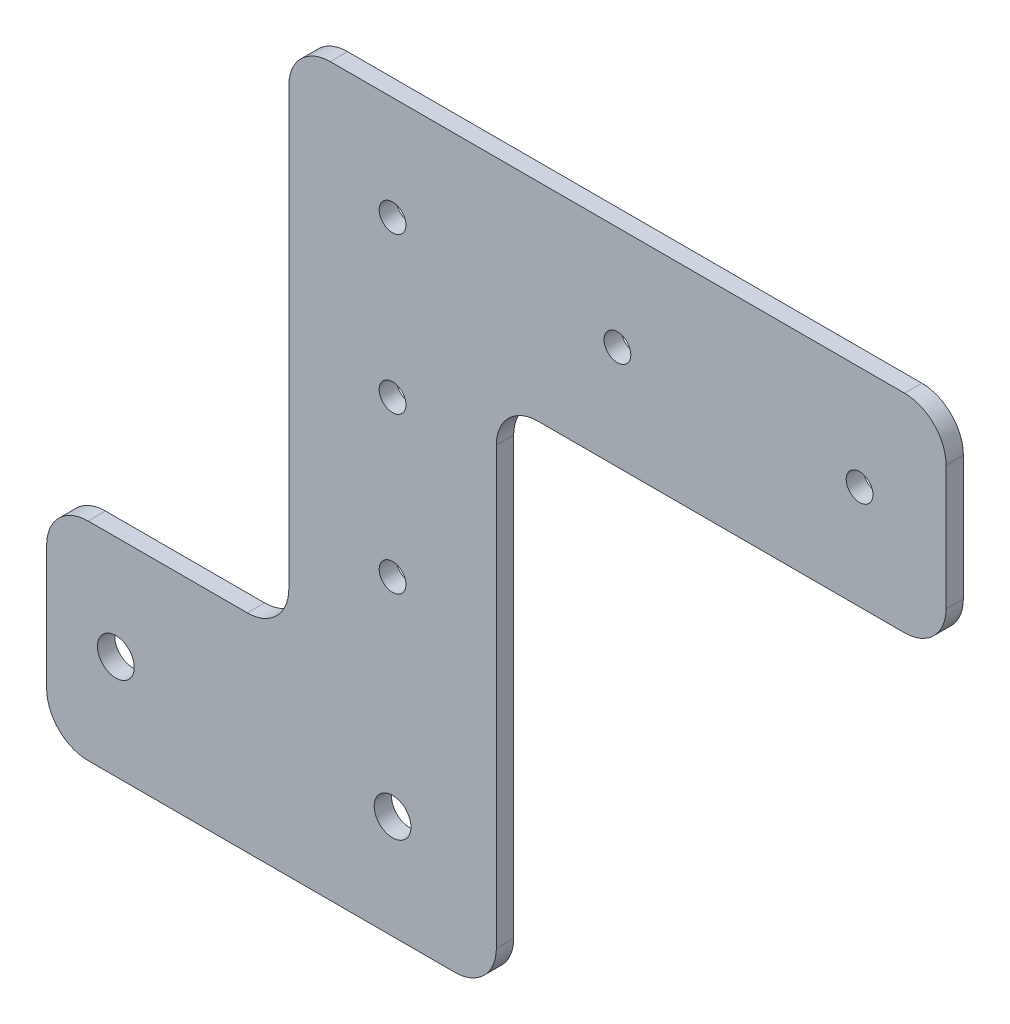
SolidWorks part; units mm, degrees
material "6061 Alloy"
ref_plane "Front Plane" through (0, 0, 0) normal (0, 0, 1) x (1, 0, 0)
ref_plane "Top Plane" through (0, 0, 0) normal (0, 1, 0) x (1, 0, 0)
ref_plane "Right Plane" through (0, 0, 0) normal (1, 0, 0) x (0, 0, -1)
sketch "Sketch1" plane through (0, 0, 0) normal (0, 0, 1) x (1, 0, 0)
  line L0 (0, 0) -> (82.55, 0)
  line L1 (82.55, 0) -> (82.55, 95.25)
  line L2 (82.55, 95.25) -> (165.1, 95.25)
  line L3 (0, 38.1) -> (44.45, 38.1)
  line L4 (44.45, 38.1) -> (44.45, 133.35)
  line L5 (44.45, 133.35) -> (165.1, 133.35)
  line L6 (0, 38.1) -> (0, 0)
  line L7 (165.1, 95.25) -> (165.1, 133.35)
  dimension "D2" = 133.35
  dimension "D3" = 82.55
  dimension "D4" = 120.65
  dimension "D1" = 38.1
extrude "Boss-Extrude1" add sketch "Sketch1" along normal blind 3.175
hole_wizard "#10 (0.1935) Diameter Hole1" positions "Sketch2" profile "Sketch3" hole size "#10" standard "ANSI Inch" end condition through all
sketch "Sketch2" plane through (0, 0, 3.175) normal (0, 0, 1) x (1, 0, 0)
  line L0 (0, 19.05) -> (63.5, 19.05) construction
  line L1 (0, 38.1) -> (0, 0) construction
  line L2 (165.1, 114.3) -> (63.5, 114.3) construction
  line L3 (165.1, 95.25) -> (165.1, 133.35) construction
  line L4 (63.5, 19.05) -> (63.5, 114.3) construction
  line L5 (44.45, 38.1) -> (82.55, 0) construction
  line L8 (165.1, 95.25) -> (165.1, 133.35) construction
  line L10 (0, 0) -> (82.55, 0) construction
  point P27 (63.5, 57.15)
  point P29 (63.5, 114.3)
  point P31 (149.225, 114.3)
  point P45 (104.775, 114.3)
  point P65 (63.5, 85.725)
  dimension "D1" = 28.575
  dimension "D3" = 15.875
  dimension "D4" = 60.325
  dimension "D6" = 57.15
sketch "Sketch3" plane through (63.5, 85.725, 3.175) normal (1, 0, 0) x (0, -1, 0)
  line L0 (0, 0) -> (0, 3.175)
  line L1 (0, 3.175) -> (2.4574, 3.175)
  line L2 (2.4574, 3.175) -> (2.4574, 0)
  line L5 (2.4574, 0) -> (0, 0)
  line L11 (0, -6.35) -> (0, 107.95) construction
  dimension "Thru Hole Dia." = 4.9149
  dimension "Thru Hole Depth" = 3.175
hole_wizard "1/4 Clearance Hole2" positions "Sketch4" profile "Sketch5" hole size "1/4" standard "ANSI Inch" end condition through all
sketch "Sketch4" plane through (0, 0, 3.175) normal (0, 0, 1) x (1, 0, 0)
  line L2 (0, 19.05) -> (82.55, 19.05) construction
  line L3 (0, 38.1) -> (0, 0) construction
  line L4 (82.55, 0) -> (82.55, 95.25) construction
  point P0 (12.7, 19.05)
  point P17 (63.5, 19.05)
  dimension "D1" = 19.05
  dimension "D2" = 69.85
sketch "Sketch5" plane through (12.7, 19.05, 3.175) normal (1, 0, 0) x (0, -1, 0)
  line L0 (0, 0) -> (0, 3.175)
  line L1 (0, 3.175) -> (3.3782, 3.175)
  line L2 (3.3782, 3.175) -> (3.3782, 0)
  line L5 (3.3782, 0) -> (0, 0)
  line L11 (0, -6.35) -> (0, 107.95) construction
  dimension "Thru Hole Dia." = 6.7564
  dimension "Thru Hole Depth" = 3.175
fillet "Fillet1" radius 7.62 8 edges at (0, 38.1, 1.5875) (44.45, 38.1, 1.5875) (44.45, 133.35, 1.5875) (165.1, 133.35, 1.5875) (165.1, 95.25, 1.5875) (82.55, 0, 1.5875) (0, 0, 1.5875) (82.55, 95.25, 1.5875)
